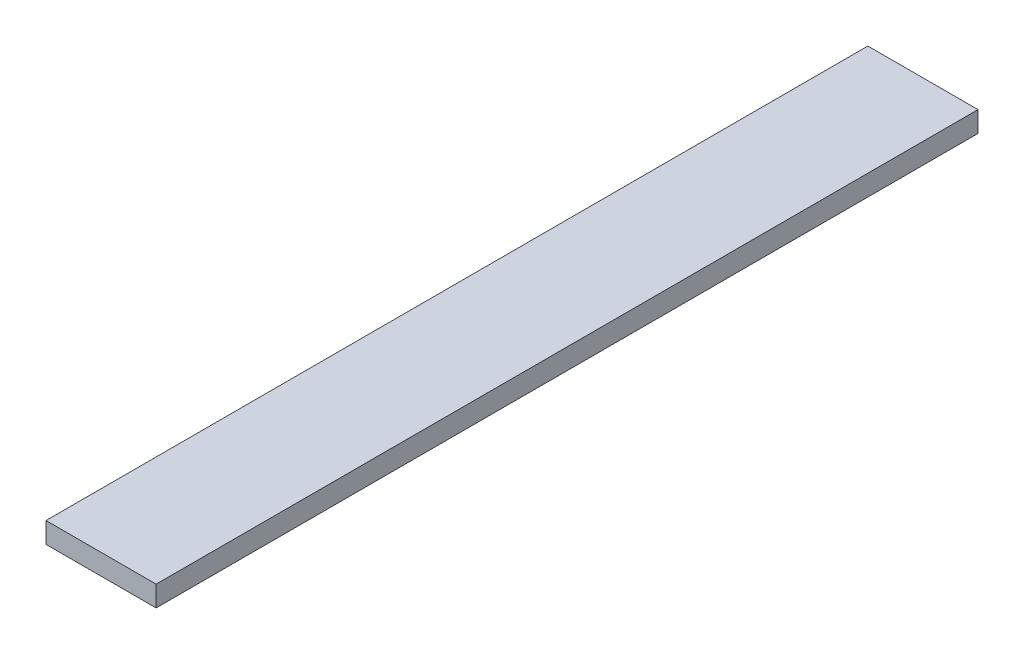
SolidWorks part; units mm, degrees
material "Pine"
ref_plane "Front Plane" through (0, 0, 0) normal (0, 0, 1) x (1, 0, 0)
ref_plane "Top Plane" through (0, 0, 0) normal (0, 1, 0) x (1, 0, 0)
ref_plane "Right Plane" through (0, 0, 0) normal (1, 0, 0) x (0, 0, -1)
sketch "Sketch1" plane through (0, 0, 0) normal (0, 1, 0) x (1, 0, 0)
  line L1 (0, 0) -> (101.6, 0)
  line L2 (0, 0) -> (0, -758.19)
  line L3 (0, -758.19) -> (101.6, -758.19)
  line L4 (101.6, 0) -> (101.6, -758.19)
  dimension "D1" = 101.6
  dimension "D2" = 758.19
extrude "Boss-Extrude1" add sketch "Sketch1" along normal blind 19.05
